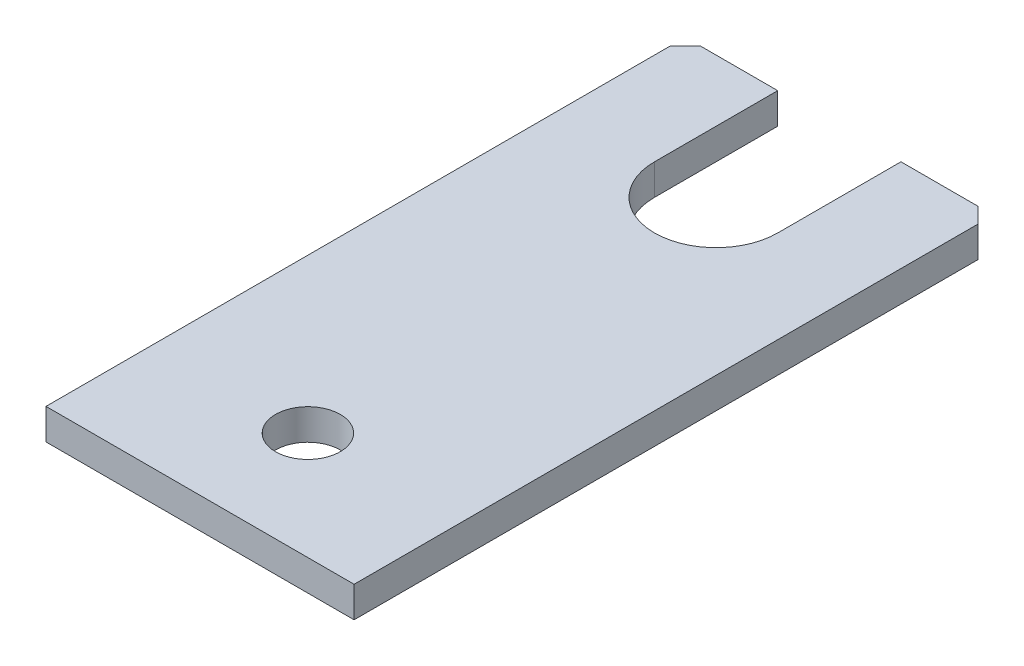
SolidWorks part; units mm, degrees
ref_plane "Спереди" through (0, 0, 0) normal (0, 0, 1) x (1, 0, 0)
ref_plane "Сверху" through (0, 0, 0) normal (0, 1, 0) x (1, 0, 0)
ref_plane "Справа" through (0, 0, 0) normal (1, 0, 0) x (0, 0, -1)
sketch "Эскиз1" plane through (0, 0, 0) normal (0, 1, 0) x (1, 0, 0)
  line L0 (0, 0) -> (20, 0)
  line L1 (20, 0) -> (20, 40.5)
  line L2 (19, 41.5) -> (14, 41.5)
  line L3 (0, 40.5) -> (0, 0)
  line L6 (6, 41.5) -> (1, 41.5)
  line L7 (1, 41.5) -> (0, 40.5)
  line L9 (6, 33.5) -> (6, 41.5)
  line L10 (14, 33.5) -> (14, 41.5)
  line L11 (20, 40.5) -> (19, 41.5)
  circle A0 centre (10, 7) radius 1
  arc A1 (6, 33.5) -> (14, 33.5) centre (10, 33.5) ccw
  point P3 (20, 41.5)
  point P4 (0, 41.5)
  dimension "D1" = 2
  dimension "D2" = 20
  dimension "D3" = 41.5
  dimension "D4" = 8
extrude "Бобышка-Вытянуть1" add sketch "Эскиз1" along normal blind 2
hole_wizard "Отверстие обработанное метчиком M51" positions "Эскиз2" profile "Эскиз3" tap size "M5" standard "ISO"
sketch "Эскиз2" plane through (0, 2, 0) normal (0, 1, 0) x (1, 0, 0)
  point P0 (10, 7)
sketch "Эскиз3" plane through (10, 2, -7) normal (1, 0, 0) x (0, 0, 1)
  line L0 (0, 0) -> (0, 15.2618)
  line L1 (0, 15.2618) -> (2.1, 14)
  line L2 (2.1, 14) -> (2.1, 0)
  line L5 (2.1, 0) -> (0, 0)
  line L10 (0, 15.2618) -> (-2.1, 14) construction
  line L11 (0, -6.35) -> (0, 107.95) construction
  dimension "Диаметр сверла" = 4.2
  dimension "Глубина сверла" = 14
  dimension "Угол заточки сверла" = 118
cosmetic thread "Отверстие резьбы1" parameters "D1"=2, "D2"=5
